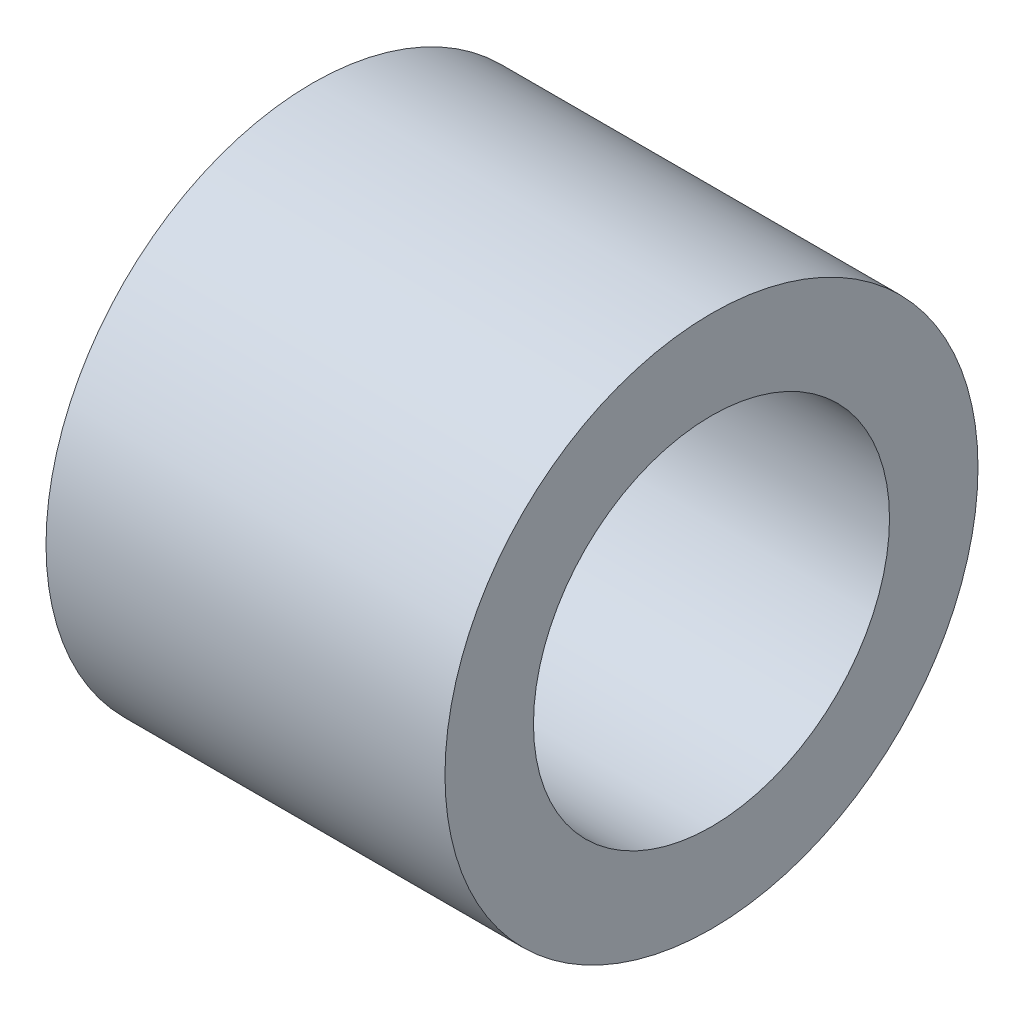
SolidWorks part; units mm, degrees
ref_plane "Front Plane" through (0, 0, 0) normal (0, 0, 1) x (1, 0, 0)
ref_plane "Top Plane" through (0, 0, 0) normal (0, 1, 0) x (1, 0, 0)
ref_plane "Right Plane" through (0, 0, 0) normal (1, 0, 0) x (0, 0, -1)
sketch "Sketch1" plane through (0, 0, 0) normal (1, 0, 0) x (0, 0, -1)
  circle A0 centre (0, 0) radius 2.125
  circle A1 centre (0, 0) radius 3.1813
  dimension "D1" = 4.25
  dimension "D2" = 6.3627
extrude "Boss-Extrude1" add sketch "Sketch1" along normal mid plane 4.7625
